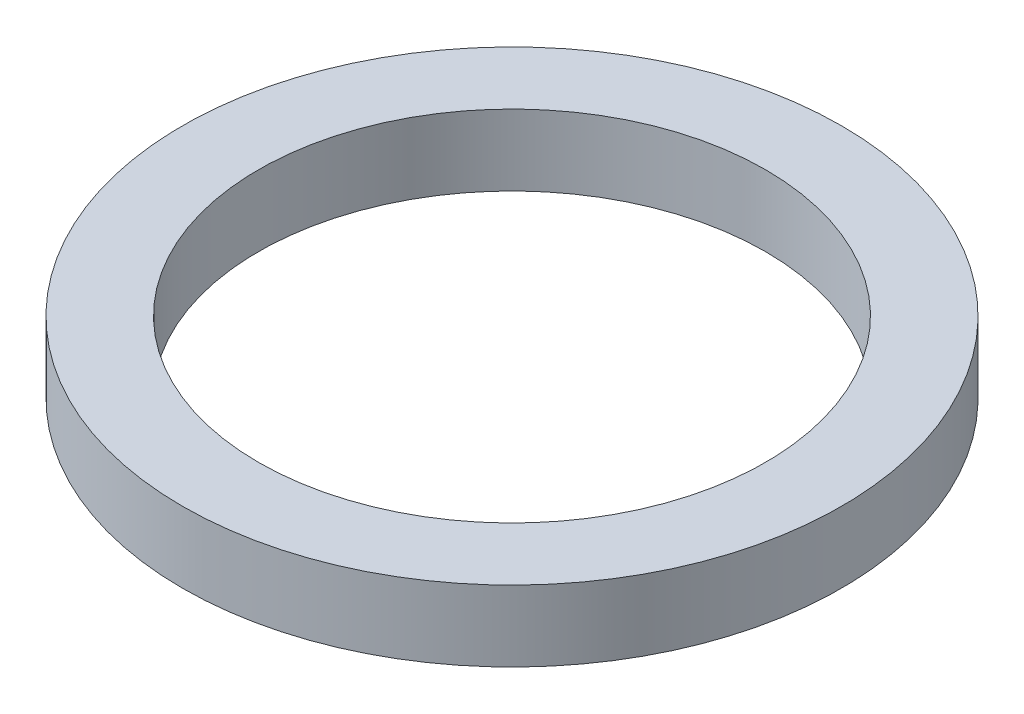
SolidWorks part; units mm, degrees
ref_plane "Front Plane" through (0, 0, 0) normal (0, 0, 1) x (1, 0, 0)
ref_plane "Top Plane" through (0, 0, 0) normal (0, 1, 0) x (1, 0, 0)
ref_plane "Right Plane" through (0, 0, 0) normal (1, 0, 0) x (0, 0, -1)
sketch "Sketch1" plane through (0, 0, 0) normal (0, 1, 0) x (1, 0, 0)
  circle A0 centre (0, 0) radius 25
  circle A1 centre (0, 0) radius 32.5
  dimension "D1" = 50
  dimension "D2" = 65
extrude "Boss-Extrude1" add sketch "Sketch1" along normal blind 7
